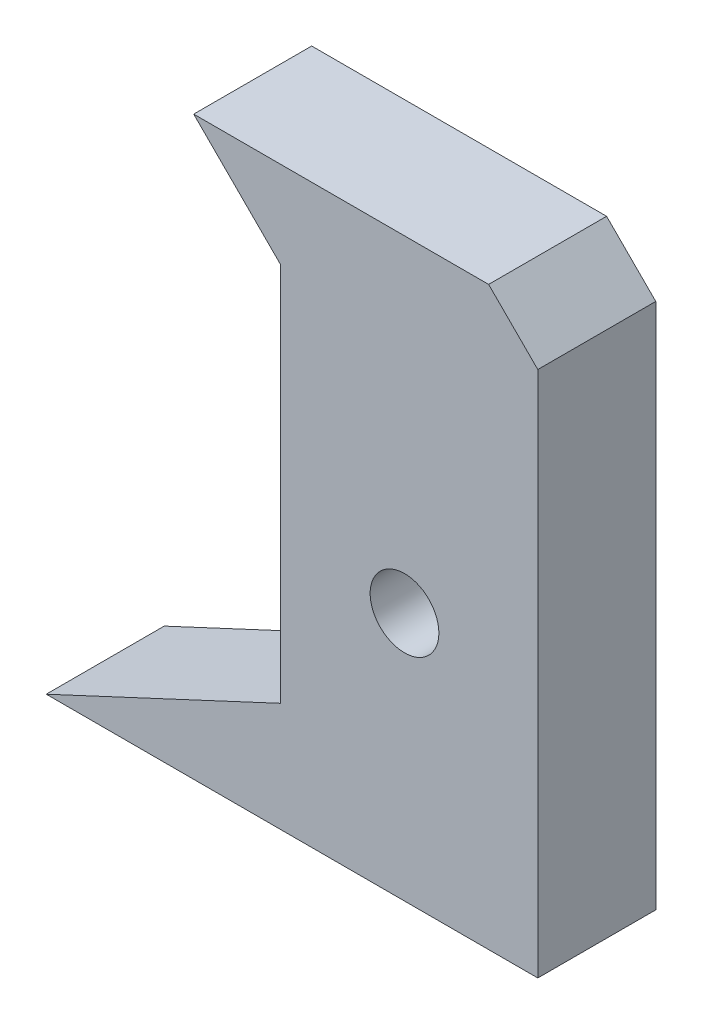
SolidWorks part; units mm, degrees
ref_plane "Front Plane" through (0, 0, 0) normal (0, 0, 1) x (1, 0, 0)
ref_plane "Top Plane" through (0, 0, 0) normal (0, 1, 0) x (1, 0, 0)
ref_plane "Right Plane" through (0, 0, 0) normal (1, 0, 0) x (0, 0, -1)
sketch "Sketch1" plane through (0, 0, 0) normal (0, 0, 1) x (1, 0, 0)
  line L0 (0, 0) -> (0, 58.6)
  line L4 (-26.196, 11.1) -> (-50, 0)
  line L5 (-50, 0) -> (0, 0)
  line L8 (0, 58.6) -> (-35, 58.6)
  line L9 (-35, 58.6) -> (-26.196, 49.796)
  line L11 (-26.196, 49.796) -> (-26.196, 11.1)
  dimension "D1" = 58.6
  dimension "D2" = 35
  dimension "D3" = 45
  dimension "D4" = 25
  dimension "D5" = 50
  dimension "D6" = 11.1
extrude "Boss-Extrude1" add sketch "Sketch1" along normal blind 12
sketch "Sketch3" plane through (0, 0, 12) normal (0, 0, 1) x (1, 0, 0)
  line L0 (-50, 0) -> (0, 0) construction
  line L1 (0, 0) -> (0, 58.6) construction
  circle A0 centre (-13.5566, 25.36) radius 3.495
  dimension "D1" = 6.99
  dimension "D2" = 25.36
  dimension "D3" = 13.5566
extrude "Cut-Extrude2" cut sketch "Sketch3" against normal through all
chamfer "Chamfer1" distance 5 angle 45 1 edges at (0, 58.6, 6)
